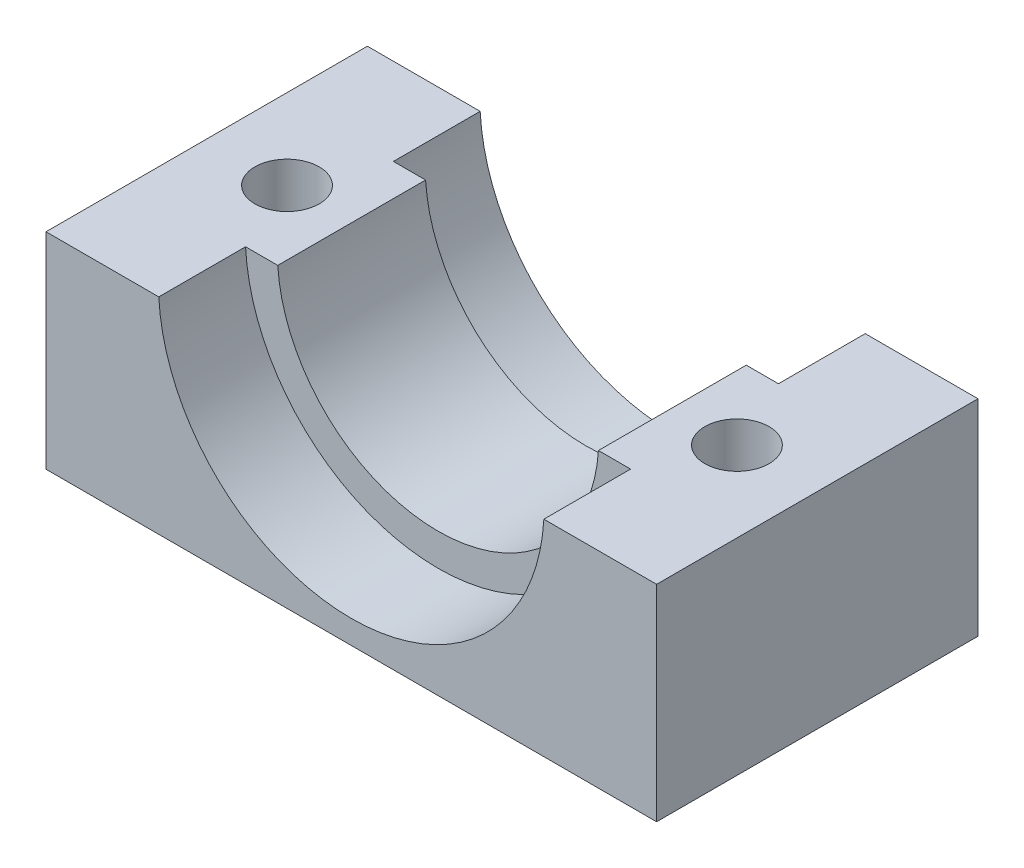
SolidWorks part; units mm, degrees
material "Nylon 6/10"
ref_plane "Front Plane" through (0, 0, 0) normal (0, 0, 1) x (1, 0, 0)
ref_plane "Top Plane" through (0, 0, 0) normal (0, 1, 0) x (1, 0, 0)
ref_plane "Right Plane" through (0, 0, 0) normal (1, 0, 0) x (0, 0, -1)
sketch "Sketch1" plane through (0, 0, 0) normal (1, 0, 0) x (0, 0, -1)
  line L0 (-25, 16) -> (25, 16)
  line L1 (-25, 16) -> (-25, -16)
  line L2 (25, 16) -> (25, -16)
  line L3 (-25, -16) -> (25, -16)
  line L4 (-25, 16) -> (25, -16) construction
  line L5 (25, 16) -> (-25, -16) construction
  point P1 (0, 0)
  dimension "D1" = 50
  dimension "D2" = 32
extrude "Boss-Extrude1" add sketch "Sketch1" along normal mid plane 95
sketch "Sketch3" plane through (0, 0, 0) normal (1, 0, 0) x (0, 0, -1)
  line L0 (-25, -12.35) -> (-11.5, -12.35)
  line L1 (-11.5, -12.35) -> (-11.5, -7.35)
  line L2 (-11.5, -7.35) -> (11.5, -7.35)
  line L3 (11.5, -7.35) -> (11.5, -12.35)
  line L4 (11.5, -12.35) -> (25, -12.35)
  line L5 (25, -12.35) -> (25, 16.5959)
  line L6 (25, 16.5959) -> (-25, 16.5959)
  line L7 (-25, 16.5959) -> (-25, -12.35)
  line L8 (20.2491, 17.65) -> (85.4, 17.65) construction
  line L9 (25, -16) -> (25, 16) construction
  line L10 (-25, 16) -> (-25, -16) construction
  line L13 (-25, -16) -> (25, -16) construction
  dimension "D1" = 33.65
  dimension "D2" = 30
  dimension "D3" = 23
  dimension "D4" = 50
revolve "Cut-Revolve1" cut sketch "Sketch3" angle 360 about L8
sketch "Sketch4" plane through (0, 16, 0) normal (0, 1, 0) x (1, 0, 0)
  line L0 (-35, 0) -> (35, 0) construction
  circle A0 centre (-35, 0) radius 5
  circle A1 centre (35, 0) radius 5
  point P4 (0, 0)
  dimension "D2" = 10
  dimension "D1" = 70
extrude "Cut-Extrude1" cut sketch "Sketch4" against normal blind 75
